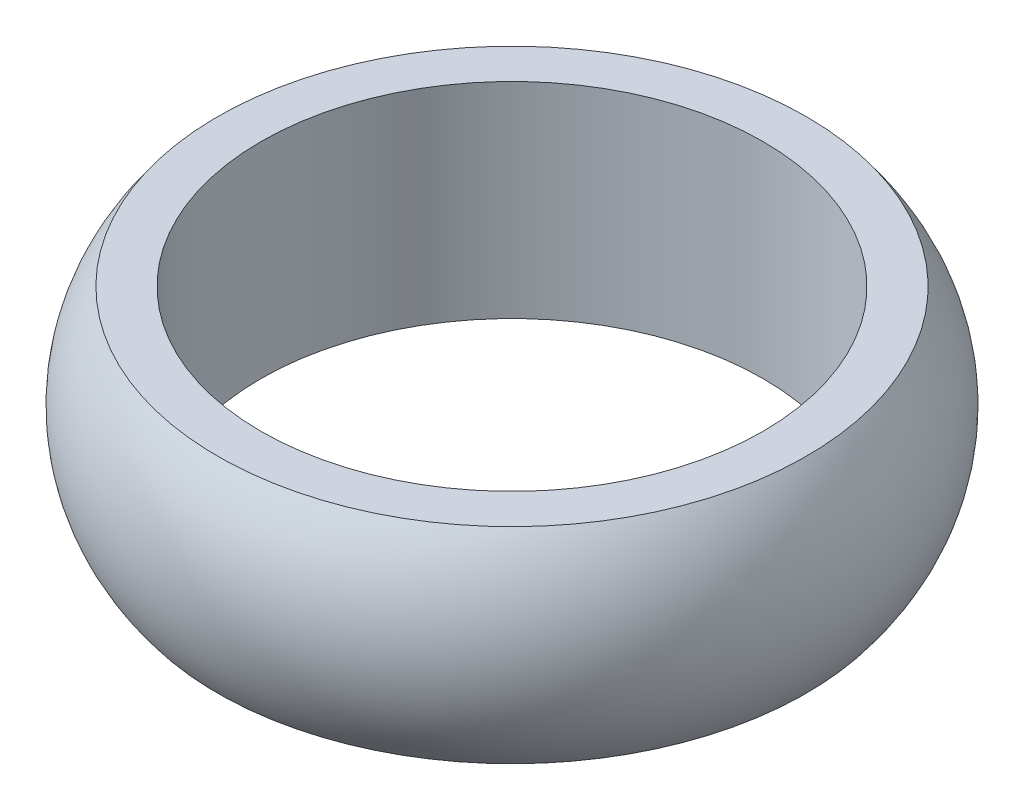
SolidWorks part; units mm, degrees
material "POLYURETHANE (11671)"
ref_plane "Front Plane" through (0, 0, 0) normal (0, 0, 1) x (1, 0, 0)
ref_plane "Top Plane" through (0, 0, 0) normal (0, 1, 0) x (1, 0, 0)
ref_plane "Right Plane" through (0, 0, 0) normal (1, 0, 0) x (0, 0, -1)
sketch "Sketch2" plane through (0, 0, 0) normal (0, 0, 1) x (1, 0, 0)
  line L0 (0, 0) -> (18.1734, 0) construction
  line L1 (15.25, 0) -> (15.25, -9.8661) construction
  line L2 (11.615, 4.75) -> (13.615, 4.75)
  line L3 (11.615, 4.75) -> (11.615, -4.75)
  line L4 (11.615, -4.75) -> (13.615, -4.75)
  line L5 (0, 0) -> (0, 8.0382) construction
  line L6 (11.615, 4.75) -> (13.615, -4.75) construction
  line L7 (11.615, -4.75) -> (13.615, 4.75) construction
  arc A0 (13.615, 4.75) -> (13.615, -4.75) centre (7.5327, 0) cw
  point P3 (12.615, 0)
  point P11 (10.75, 7.2474)
  dimension "D1" = 15.25
  dimension "D2" = 11.615
  dimension "D3" = 2
  dimension "D4" = 9.5
revolve "Revolve1" add sketch "Sketch2" angle 360 about L5
